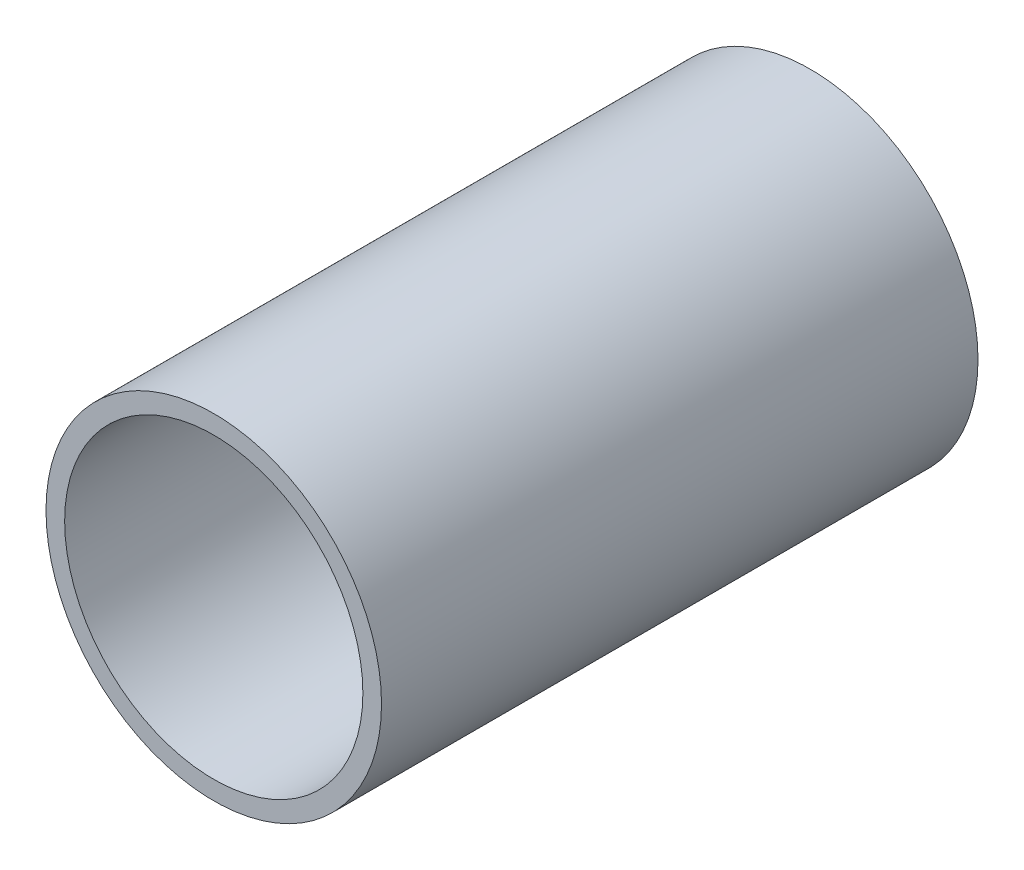
SolidWorks part; units mm, degrees
material "PVC Rigid"
ref_plane "Front Plane" through (0, 0, 0) normal (0, 0, 1) x (1, 0, 0)
ref_plane "Top Plane" through (0, 0, 0) normal (0, 1, 0) x (1, 0, 0)
ref_plane "Right Plane" through (0, 0, 0) normal (1, 0, 0) x (0, 0, -1)
sketch "Sketch1" plane through (0, 0, 0) normal (0, 0, 1) x (1, 0, 0)
  circle A0 centre (0, 0) radius 50.8
  circle A1 centre (0, 0) radius 57.15
  dimension "D1" = 101.6
  dimension "D2" = 114.3
extrude "Boss-Extrude1" add sketch "Sketch1" along normal blind 203.2
